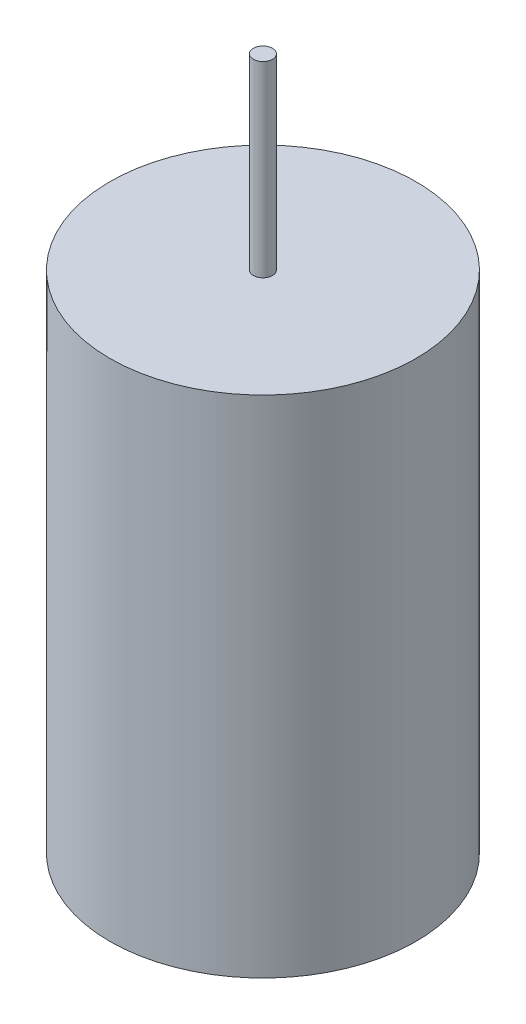
SolidWorks part; units mm, degrees
ref_plane "Front Plane" through (0, 0, 0) normal (0, 0, 1) x (1, 0, 0)
ref_plane "Top Plane" through (0, 0, 0) normal (0, 1, 0) x (1, 0, 0)
ref_plane "Right Plane" through (0, 0, 0) normal (1, 0, 0) x (0, 0, -1)
sketch "Sketch1" plane through (0, 0, 0) normal (0, 1, 0) x (1, 0, 0)
  circle A0 centre (0, 0) radius 18.8
  dimension "D1" = 37.6
extrude "Boss-Extrude1" add sketch "Sketch1" against normal blind 62
sketch "Sketch2" plane through (0, 0, 0) normal (0, 1, 0) x (1, 0, 0)
  circle A0 centre (0, 0) radius 1.17
  dimension "D1" = 2.34
extrude "Boss-Extrude2" add sketch "Sketch2" along normal blind 23
